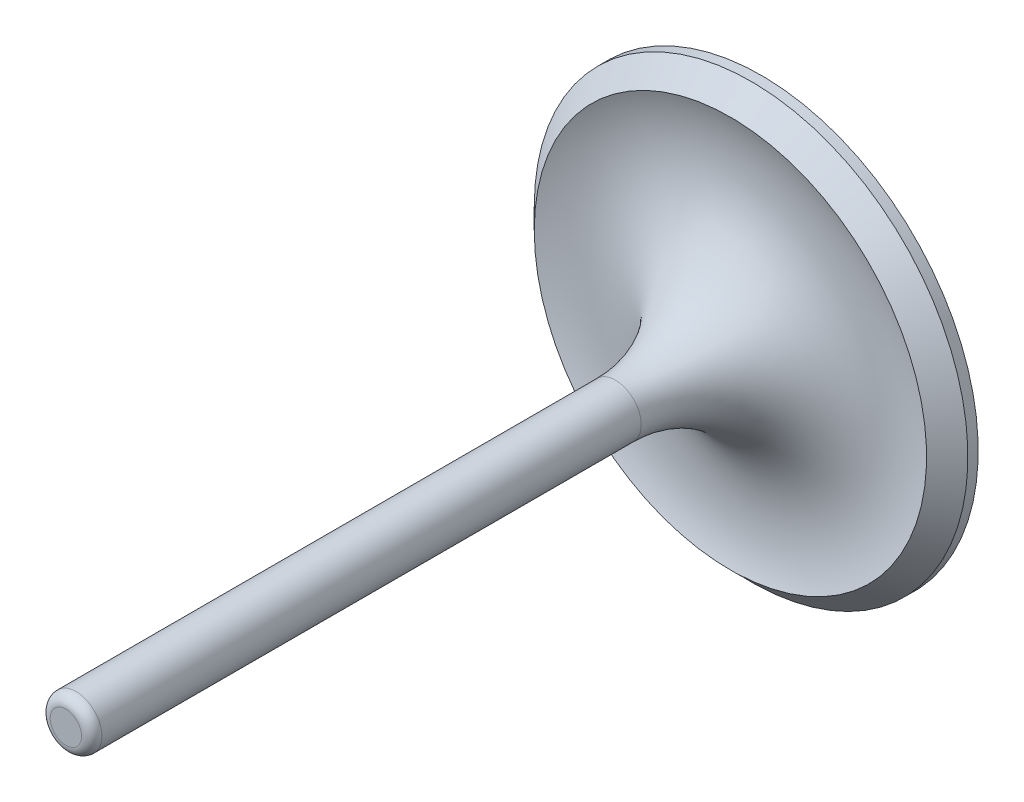
SolidWorks part; units mm, degrees
ref_plane "Front Plane" through (0, 0, 0) normal (1, 0, 0) x (0, 1, 0)
ref_plane "Top Plane" through (0, 0, 0) normal (0, 0, 1) x (0, 1, 0)
ref_plane "Right Plane" through (0, 0, 0) normal (0, 1, 0) x (-1, 0, 0)
sketch "Sketch1" plane through (0, 0, 0) normal (1, 0, 0) x (0, 1, 0)
  line L0 (0, 0) -> (0, 85.55)
  line L1 (0, 85.55) -> (3.18, 85.55)
  line L2 (3.18, 85.55) -> (3.18, 17.9547)
  line L3 (24.13, 3.81) -> (26.67, 1.27)
  line L4 (26.67, 1.27) -> (26.67, 0)
  line L5 (26.67, 0) -> (0, 0)
  arc A0 (3.18, 17.9547) -> (24.13, 3.81) centre (18.43, 17.9547) ccw
  dimension "D4" = 85.55
  dimension "D7" = 15.25
  dimension "D1" = 26.67
  dimension "D2" = 1.27
  dimension "D3" = 3.81
  dimension "D5" = 45
  dimension "D6" = 3.18
revolve "Revolve1" add sketch "Sketch1" angle 360 about L0
fillet "Fillet1" radius 1.25 1 edges at (-3.18, 0, 85.55)
